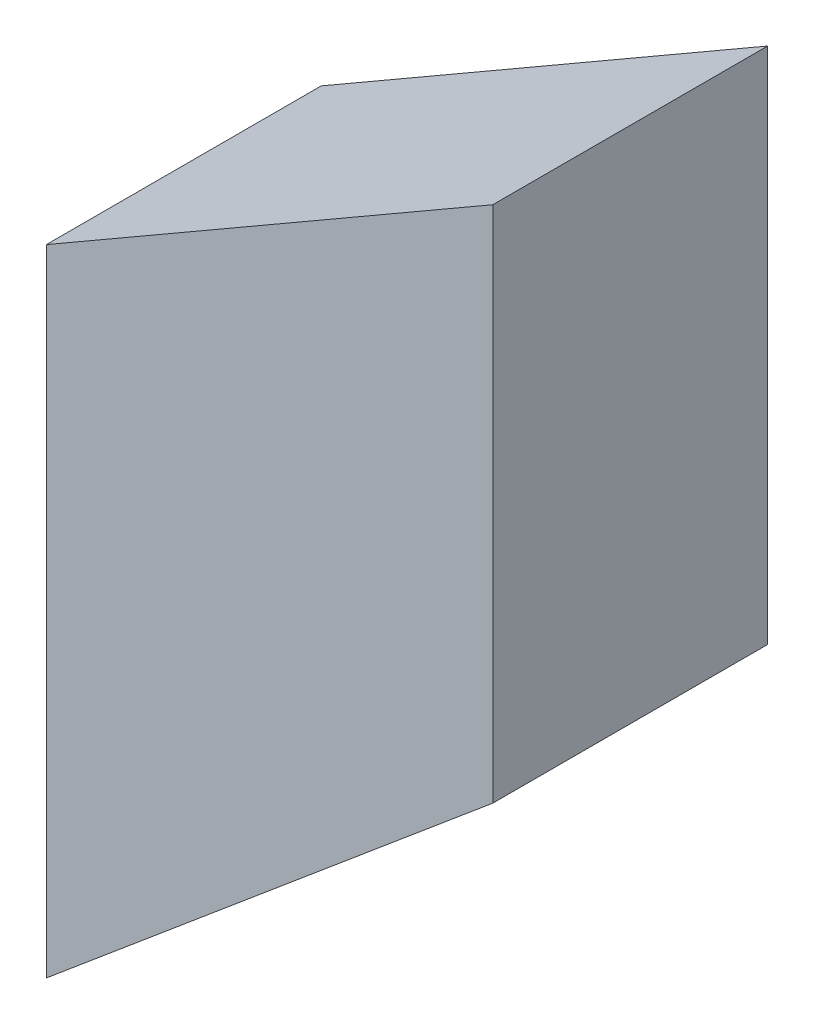
SolidWorks part; units mm, degrees
ref_plane "Front Plane" through (0, 0, 0) normal (0, 0, 1) x (1, 0, 0)
ref_plane "Top Plane" through (0, 0, 0) normal (0, 1, 0) x (1, 0, 0)
ref_plane "Right Plane" through (0, 0, 0) normal (1, 0, 0) x (0, 0, -1)
sketch "Sketch1" plane through (0, 0, 0) normal (0, 0, 1) x (1, 0, 0)
  line L0 (0, 25575.7568) -> (0, 60960)
  line L1 (0, 0) -> (-30480, 0) construction
  line L2 (0, 60960) -> (-30480, 43362.3638)
  line L3 (-30480, 43362.3638) -> (-30480, 0)
  line L5 (-30480, 0) -> (0, 25575.7568)
  line L6 (0, 0) -> (0, 60960) construction
  dimension "D1" = 60960
  dimension "D2" = 30480
  dimension "D3" = 40
  dimension "D4" = 30
extrude "Boss-Extrude1" add sketch "Sketch1" against normal blind 18769.584
equation "\"D1@Boss-Extrude1\"=61.58"
equation "\"Height\"= 200"
equation "\"Radius\"= 100"
equation "\"Added Height\"= .0001"
equation "\"Angle of Repose\"= 30"
equation "\"Shear Angle\"= 40"
equation "\"D2@Sketch1\"=\"Radius\""
equation "\"D1@Sketch1\"=\"Height\""
equation "\"D4@Sketch1\"=\"Angle of Repose\""
equation "\"D3@Sketch1\"=\"Shear Angle\""
